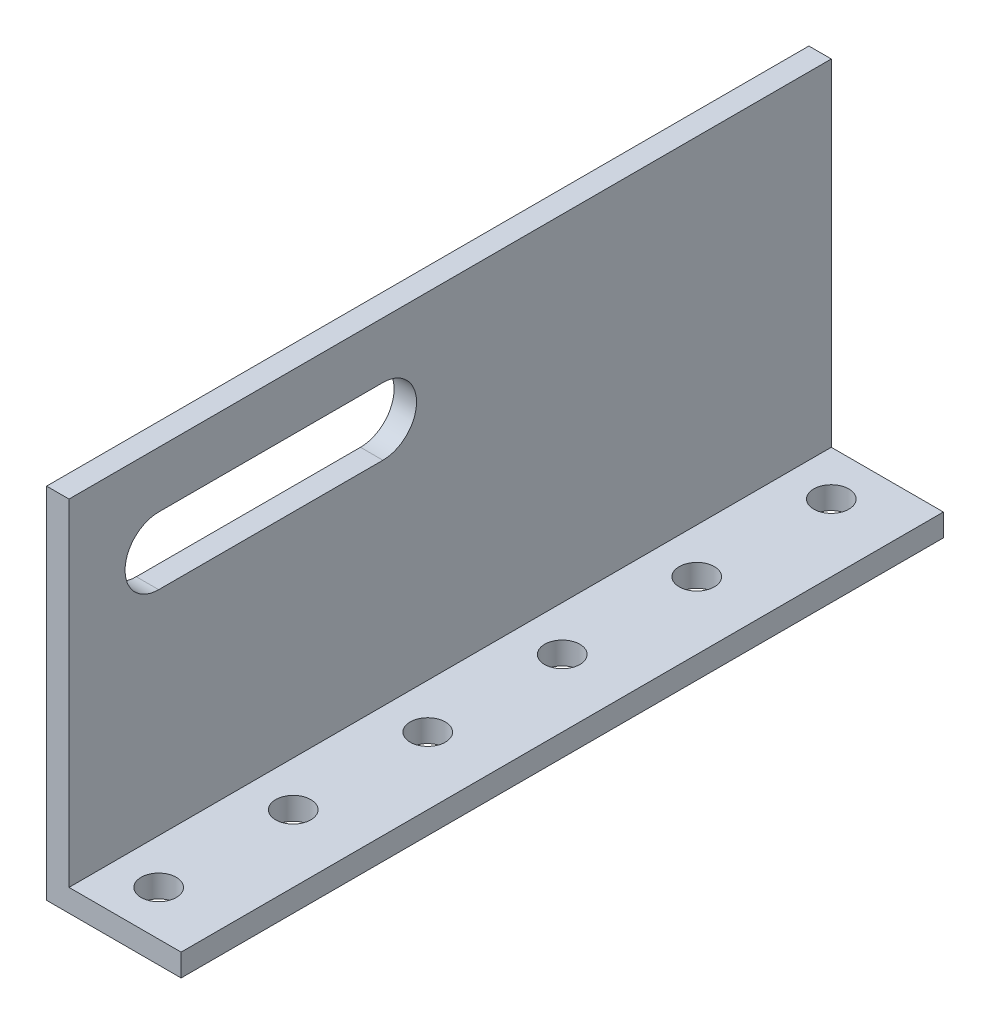
SolidWorks part; units mm, degrees
material "6061-T6 (SS)"
ref_plane "Front Plane" through (0, 0, 0) normal (0, 0, 1) x (1, 0, 0)
ref_plane "Top Plane" through (0, 0, 0) normal (0, 1, 0) x (1, 0, 0)
ref_plane "Right Plane" through (0, 0, 0) normal (1, 0, 0) x (0, 0, -1)
sketch "Sketch1" plane through (0, 0, 0) normal (0, 0, 1) x (1, 0, 0)
  line L1 (0, 0) -> (3.175, 0)
  line L2 (0, 0) -> (0, 50.8)
  line L3 (0, 50.8) -> (3.175, 50.8)
  line L4 (3.175, 0) -> (3.175, 50.8)
  line L5 (0, 0) -> (19.05, 0)
  line L6 (0, 0) -> (0, 3.175)
  line L7 (0, 3.175) -> (19.05, 3.175)
  line L8 (19.05, 0) -> (19.05, 3.175)
  dimension "D1" = 3.175
  dimension "D2" = 3.175
  dimension "D3" = 19.05
  dimension "D4" = 50.8
extrude "Boss-Extrude1" add sketch "Sketch1" along normal blind 107.95 contours L2 L7 L4 L3 | L7 L2 L1 L4 | L5 L8 L7 L4
sketch "Sketch2" plane through (0, 3.175, 0) normal (0, 1, 0) x (1, 0, 0)
  line L1 (3.175, 0) -> (19.05, 0) construction
  line L2 (3.175, -107.95) -> (3.175, 0) construction
  circle A0 centre (9.525, -6.35) radius 2.4892
  circle A1 centre (9.525, -25.4) radius 2.4892
  circle A2 centre (9.525, -44.45) radius 2.4892
  circle A3 centre (9.525, -63.5) radius 2.4892
  circle A4 centre (9.525, -82.55) radius 2.4892
  circle A5 centre (9.525, -101.6) radius 2.4892
  dimension "D2" = 4.9784
  dimension "D3" = 6.35
  dimension "D5" = 19.05
  dimension "D1" = 6.35
  dimension "D4" = 6
extrude "Cut-Extrude1" cut sketch "Sketch2" against normal blind 107.95
sketch "Sketch3" plane through (0, 0, 0) normal (-1, 0, 0) x (0, 0, 1)
  line L0 (63.5, 38.1) -> (95.25, 38.1) construction
  line L1 (63.5, 42.8625) -> (95.25, 42.8625)
  line L2 (63.5, 33.3375) -> (95.25, 33.3375)
  line L3 (107.95, 0) -> (107.95, 50.8) construction
  line L4 (107.95, 50.8) -> (0, 50.8) construction
  arc A0 (63.5, 42.8625) -> (63.5, 33.3375) centre (63.5, 38.1) ccw
  arc A1 (95.25, 33.3375) -> (95.25, 42.8625) centre (95.25, 38.1) ccw
  point P2 (79.375, 38.1)
  dimension "D2" = 4.7625
  dimension "D1" = 12.7
  dimension "D3" = 31.75
  dimension "D4" = 12.7
extrude "Cut-Extrude2" cut sketch "Sketch3" against normal blind 165.1
equation "\"`\"=1.56032"
